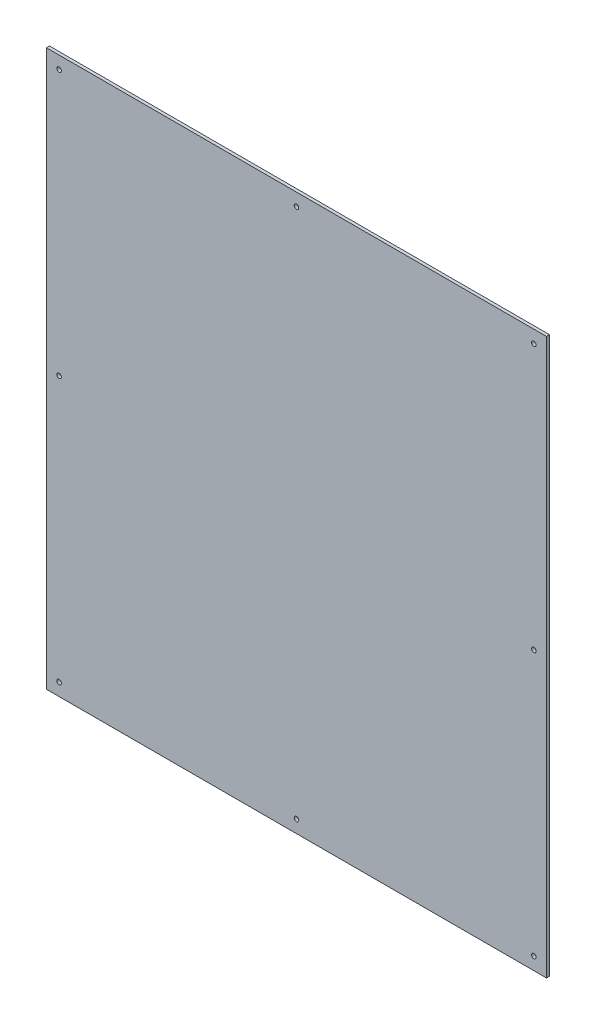
SolidWorks part; units mm, degrees
material "Acrylic (Medium-high impact)"
ref_plane "Front Plane" through (0, 0, 0) normal (0, 0, 1) x (1, 0, 0)
ref_plane "Top Plane" through (0, 0, 0) normal (0, 1, 0) x (1, 0, 0)
ref_plane "Right Plane" through (0, 0, 0) normal (1, 0, 0) x (0, 0, -1)
sketch "Sketch1" plane through (0, 0, 0) normal (0, 0, 1) x (1, 0, 0)
  line L1 (0, 0) -> (495, 0)
  line L2 (0, 0) -> (0, 550)
  line L3 (0, 550) -> (495, 550)
  line L4 (495, 0) -> (495, 550)
  line L5 (495, 0) -> (495, 250) construction
  line L6 (0, 550) -> (500, 550) construction
extrude "Boss-Extrude1" add sketch "Sketch1" along normal blind 3
hole_wizard "M4 Clearance Hole1" positions "Sketch2" profile "Sketch3" hole size "M4" standard "ANSI Metric" end condition through all
sketch "Sketch2" plane through (0, 0, 3) normal (0, 0, 1) x (1, 0, 0)
  line L1 (495, 550) -> (0, 550) construction
  line L2 (0, 550) -> (0, 0) construction
  line L3 (0, 0) -> (495, 0) construction
  line L4 (495, 0) -> (495, 550) construction
  point P0 (12.5, 275)
  point P2 (12.5, 537.5)
  point P4 (12.5, 12.5)
  point P6 (247.5, 12.5)
  point P10 (482.5, 12.5)
  point P12 (482.5, 275)
  point P14 (482.5, 537.5)
  point P16 (247.5, 537.5)
  point P40 (0, 275)
  point P42 (247.5, 0)
  dimension "D1" = 12.5
  dimension "D2" = 12.5
  dimension "D3" = 12.5
  dimension "D4" = 12.5
sketch "Sketch3" plane through (12.5, 275, 3) normal (1, 0, 0) x (0, -1, 0)
  line L0 (0, 0) -> (0, 3)
  line L1 (0, 3) -> (2.25, 3)
  line L2 (2.25, 3) -> (2.25, 0)
  line L5 (2.25, 0) -> (0, 0)
  line L11 (0, -6.35) -> (0, 107.95) construction
  dimension "Thru Hole Dia." = 4.5
  dimension "Thru Hole Depth" = 3
